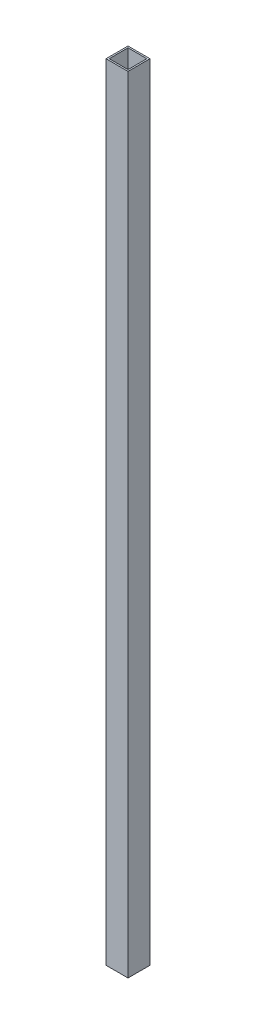
SolidWorks part; units mm, degrees
ref_plane "Front Plane" through (0, 0, 0) normal (0, 0, 1) x (1, 0, 0)
ref_plane "Top Plane" through (0, 0, 0) normal (0, 1, 0) x (1, 0, 0)
ref_plane "Right Plane" through (0, 0, 0) normal (1, 0, 0) x (0, 0, -1)
sketch "Sketch1" plane through (0, 0, 0) normal (0, 1, 0) x (1, 0, 0)
  line L0 (-1, -1) -> (-13, -1)
  line L1 (0, 0) -> (-14, 0)
  line L2 (0, 0) -> (0, -14)
  line L3 (0, -14) -> (-14, -14)
  line L4 (-14, 0) -> (-14, -14)
  line L5 (-13, -1) -> (-13, -13)
  line L6 (-1, -13) -> (-13, -13)
  line L7 (-1, -1) -> (-1, -13)
  dimension "D1" = 14
  dimension "D2" = 14
  dimension "D3" = 1
extrude "Boss-Extrude1" add sketch "Sketch1" along normal blind 500
